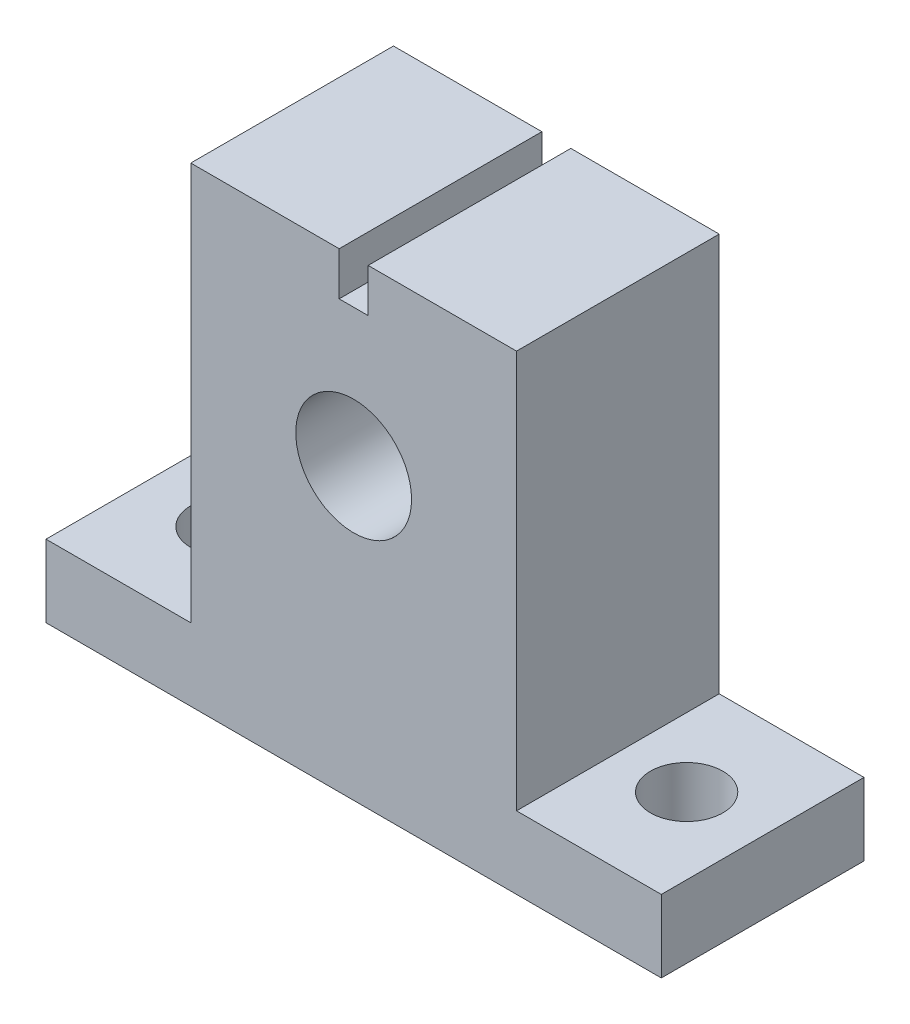
SolidWorks part; units mm, degrees
ref_plane "Front Plane" through (0, 0, 0) normal (0, 0, 1) x (1, 0, 0)
ref_plane "Top Plane" through (0, 0, 0) normal (0, 1, 0) x (1, 0, 0)
ref_plane "Right Plane" through (0, 0, 0) normal (1, 0, 0) x (0, 0, -1)
sketch "Sketch1" plane through (0, 0, 0) normal (0, 0, 1) x (1, 0, 0)
  line L0 (0, 0) -> (42.5, 0)
  line L1 (42.5, 0) -> (42.5, 5)
  line L2 (42.5, 5) -> (32.5, 5)
  line L3 (32.5, 5) -> (32.5, 32.5)
  line L4 (32.5, 32.5) -> (10, 32.5)
  line L5 (10, 32.5) -> (10, 5)
  line L6 (10, 5) -> (0, 5)
  line L7 (0, 5) -> (0, 0)
  line L8 (21.25, 0) -> (21.25, 37.1738) construction
  dimension "D1" = 42.5
  dimension "D2" = 32.5
  dimension "D3" = 10
  dimension "D4" = 5
  dimension "D5" = 5
extrude "Boss-Extrude1" add sketch "Sketch1" along normal blind 14
sketch "Sketch2" plane through (0, 0, 14) normal (0, 0, 1) x (1, 0, 0)
  line L0 (21.25, 32.5) -> (21.25, 0) construction
  line L1 (32.5, 32.5) -> (10, 32.5) construction
  line L4 (0, 0) -> (42.5, 0) construction
  circle A0 centre (21.25, 20) radius 4
  dimension "D1" = 8
  dimension "D2" = 20
extrude "Cut-Extrude1" cut sketch "Sketch2" against normal through all
sketch "Sketch3" plane through (0, 5, 0) normal (0, 1, 0) x (1, 0, 0)
  line L0 (42.5, -7) -> (32.5, -7) construction
  line L1 (42.5, -14) -> (42.5, 0) construction
  line L2 (32.5, -14) -> (32.5, 0) construction
  line L3 (21.4296, 0) -> (21.25, 0)
  line L4 (32.5, 0) -> (10, 0) construction
  circle A0 centre (37.5, -7) radius 2.5
  circle A1 centre (5.5, -7) radius 2.5
  dimension "D1" = 5
  dimension "D2" = 32
extrude "Cut-Extrude2" cut sketch "Sketch3" against normal blind 14 contours A1
sketch "Sketch4" plane through (0, 5, 0) normal (0, 1, 0) x (1, 0, 0)
  circle A0 centre (37.25, -7) radius 2.5
extrude "Cut-Extrude3" cut sketch "Sketch4" against normal blind 14
sketch "Sketch5" plane through (0, 32.5, 0) normal (0, 1, 0) x (1, 0, 0)
  line L1 (32.5, 0) -> (10, 0) construction
  line L4 (22.25, -14) -> (20.25, -14)
  line L5 (22.25, -14) -> (22.25, 0)
  line L6 (22.25, 0) -> (20.25, 0)
  line L7 (20.25, -14) -> (20.25, 0)
  line L8 (22.25, -14) -> (20.25, 0) construction
  line L9 (22.25, 0) -> (20.25, -14) construction
  point P6 (21.25, -7)
  dimension "D1" = 2
extrude "Cut-Extrude4" cut sketch "Sketch5" against normal blind 3
